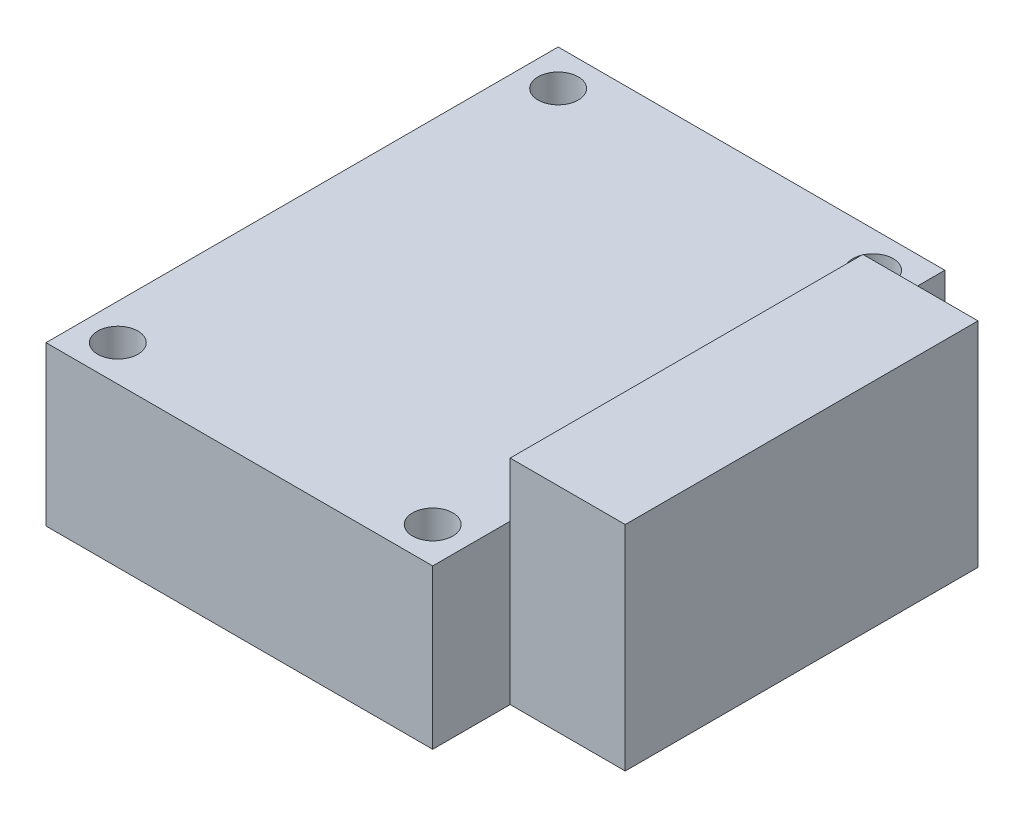
SolidWorks part; units mm, degrees
ref_plane "Front Plane" through (0, 0, 0) normal (0, 0, 1) x (1, 0, 0)
ref_plane "Top Plane" through (0, 0, 0) normal (0, 1, 0) x (1, 0, 0)
ref_plane "Right Plane" through (0, 0, 0) normal (1, 0, 0) x (0, 0, -1)
sketch "Sketch1" plane through (0, 0, 0) normal (0, 1, 0) x (1, 0, 0)
  line L0 (-16.8, 22.25) -> (-13.68, 22.25) construction
  line L1 (-16.8, -22.25) -> (16.8, -22.25)
  line L2 (-16.8, -22.25) -> (-16.8, 22.25)
  line L3 (-16.8, 22.25) -> (16.8, 22.25)
  line L4 (16.8, -22.25) -> (16.8, 22.25)
  line L5 (-16.8, -22.25) -> (16.8, 22.25) construction
  line L6 (-16.8, 22.25) -> (16.8, -22.25) construction
  line L7 (-13.68, 22.25) -> (-13.68, 19.13) construction
  line L8 (-16.8, -22.25) -> (-13.68, -22.25) construction
  line L9 (-13.68, -22.25) -> (-13.68, -19.13) construction
  line L10 (16.8, -19.13) -> (13.68, -19.13) construction
  circle A0 centre (-13.68, 19.13) radius 1.75
  circle A1 centre (-13.68, -19.13) radius 1.75
  circle A2 centre (13.68, -19.13) radius 1.75
  circle A3 centre (13.68, 19.13) radius 1.75
  point P0 (0, 0)
extrude "Boss-Extrude1" add sketch "Sketch1" along normal blind 13.8
sketch "Sketch2" plane through (16.8, 0, 0) normal (1, 0, 0) x (0, 0, -1)
  line L0 (22.25, 0) -> (15.13, 0) construction
  line L1 (-22.25, 0) -> (22.25, 0) construction
  line L2 (15.13, 0) -> (15.13, 8.55) construction
  line L3 (15.13, 8.55) -> (-15.52, 8.55) construction
  line L4 (-15.52, 0) -> (-15.52, 8.55) construction
  line L6 (-15.52, 8.55) -> (15.13, 8.55)
  line L7 (-15.52, 8.55) -> (-15.52, 0)
  line L8 (-15.52, 0) -> (15.13, 0)
  line L9 (15.13, 8.55) -> (15.13, 0)
  line L10 (-15.52, 8.55) -> (15.13, 0) construction
  line L11 (-15.52, 0) -> (15.13, 8.55) construction
  point P9 (-0.195, 4.275)
extrude "Boss-Extrude2" add sketch "Sketch2" along normal blind 10
sketch "Sketch3" plane through (0, 8.55, 0) normal (0, 1, 0) x (1, 0, 0)
  line L1 (16.8, 15.13) -> (26.8, 15.13)
  line L2 (16.8, 15.13) -> (16.8, -15.52)
  line L3 (16.8, -15.52) -> (26.8, -15.52)
  line L4 (26.8, 15.13) -> (26.8, -15.52)
  line L5 (16.8, 15.13) -> (26.8, -15.52) construction
  line L6 (16.8, -15.52) -> (26.8, 15.13) construction
  point P4 (21.8, -0.195)
extrude "Boss-Extrude3" add sketch "Sketch3" along normal blind 10
